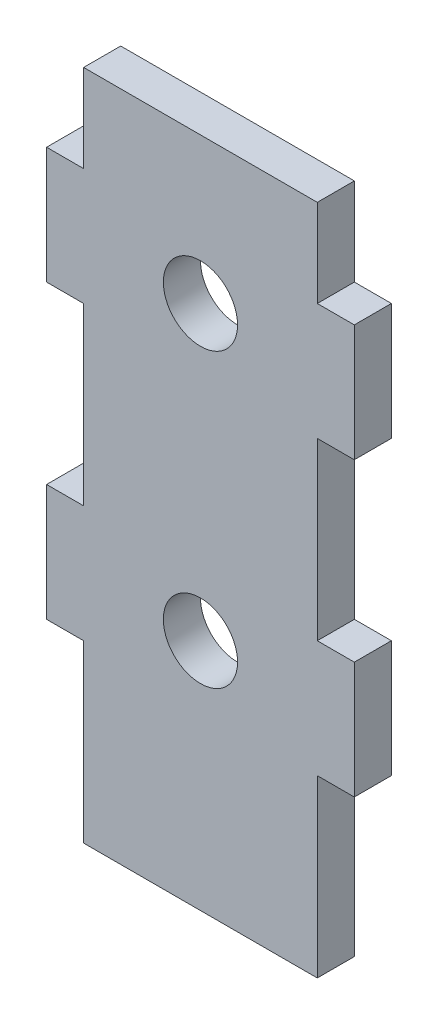
SolidWorks part; units mm, degrees
material "ABS"
ref_plane "Front Plane" through (0, 0, 0) normal (0, 0, 1) x (1, 0, 0)
ref_plane "Top Plane" through (0, 0, 0) normal (0, 1, 0) x (1, 0, 0)
ref_plane "Right Plane" through (0, 0, 0) normal (1, 0, 0) x (0, 0, -1)
sketch "Sketch1" plane through (0, 0, 0) normal (0, 0, 1) x (1, 0, 0)
  line L0 (-20, 0) -> (20, 0)
  line L1 (20, 0) -> (20, 30)
  line L2 (20, 30) -> (26.34, 30)
  line L3 (26.34, 30) -> (26.34, 50)
  line L4 (26.34, 50) -> (20, 50)
  line L5 (20, 50) -> (20, 80)
  line L6 (20, 80) -> (26.34, 80)
  line L7 (26.34, 80) -> (26.34, 100)
  line L8 (26.34, 100) -> (20, 100)
  line L9 (20, 100) -> (20, 115)
  line L10 (20, 115) -> (-20, 115)
  line L11 (0, 115) -> (0, 0) construction
  line L12 (-20, 100) -> (-20, 115)
  line L13 (-26.34, 100) -> (-20, 100)
  line L14 (-26.34, 80) -> (-26.34, 100)
  line L15 (-20, 80) -> (-26.34, 80)
  line L16 (-20, 50) -> (-20, 80)
  line L17 (-26.34, 50) -> (-20, 50)
  line L18 (-26.34, 30) -> (-26.34, 50)
  line L19 (-20, 30) -> (-26.34, 30)
  line L20 (-20, 0) -> (-20, 30)
  dimension "D1" = 20
  dimension "D2" = 20
  dimension "D3" = 15
  dimension "D4" = 6.34
  dimension "D5" = 6.34
  dimension "D6" = 6.34
  dimension "D7" = 6.34
  dimension "D8" = 20
  dimension "D9" = 20
  dimension "D10" = 30
  dimension "D11" = 30
extrude "Boss-Extrude1" add sketch "Sketch1" along normal blind 6.35
sketch "Sketch3" plane through (0, 0, 6.35) normal (0, 0, 1) x (1, 0, 0)
  line L0 (20, 115) -> (-20, 115) construction
  line L1 (-26.34, 100) -> (-26.34, 80) construction
  line L2 (-26.34, 50) -> (-26.34, 30) construction
  circle A0 centre (0, 90) radius 6.35
  circle A1 centre (0, 40) radius 6.35
  dimension "D1" = 25
  dimension "D2" = 50
  dimension "D3" = 12.7
  dimension "D4" = 12.7
  dimension "D5" = 26.34
  dimension "D6" = 26.34
extrude "Cut-Extrude1" cut sketch "Sketch3" against normal through all both and the other way through all
